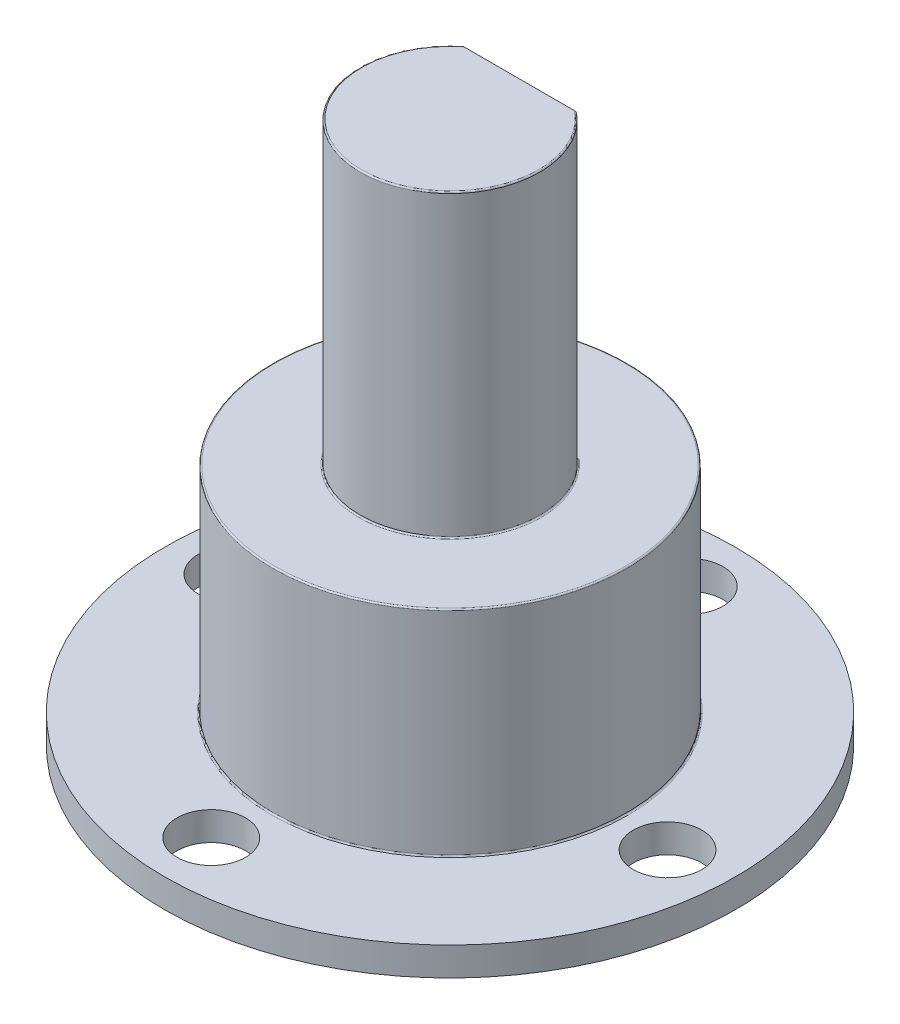
SolidWorks part; units mm, degrees
material "ABS"
ref_plane "Plan de face" through (0, 0, 0) normal (0, 0, 1) x (1, 0, 0)
ref_plane "Plan de dessus" through (0, 0, 0) normal (0, 1, 0) x (1, 0, 0)
ref_plane "Plan de droite" through (0, 0, 0) normal (1, 0, 0) x (0, 0, -1)
sketch "Esquisse2" plane through (0, 0, 0) normal (0, 0, 1) x (1, 0, 0)
  line L0 (0, 19) -> (3.15, 19)
  line L3 (6.2, 3) -> (6.2, 1)
  line L4 (6.2, 1) -> (10, 1)
  line L5 (10, 1) -> (10, 0)
  line L6 (10, 0) -> (4.5, 0)
  line L7 (4.5, 0) -> (4.5, 5)
  line L8 (4.5, 5) -> (0, 5)
  line L9 (0, 5) -> (0, 19)
  line L11 (3.15, 19) -> (3.15, 8.5)
  line L12 (3.15, 8.5) -> (6.2, 8.5)
  line L13 (6.2, 3) -> (6.2, 8.5)
  point P2 (1.575, 19)
  dimension "D1" = 10
  dimension "D2" = 19
  dimension "D3" = 0
  dimension "D4" = 1
  dimension "D5" = 4.5
  dimension "D6" = 2
  dimension "D7" = 8.5
  dimension "D8" = 5
  dimension "D9" = 3.15
  dimension "D10" = 0
  dimension "D12" = 1.7
revolve "Révolution2" add sketch "Esquisse2" angle 360 about L9
sketch "Esquisse3" plane through (0, 19, 0) normal (0, 1, 0) x (1, 0, 0)
  line L1 (-3.6413, 2.4219) -> (2.9365, 2.4219)
  line L2 (-3.6413, 2.4219) -> (-3.6413, 3.808)
  line L3 (-3.6413, 3.808) -> (2.9365, 3.808)
  line L4 (2.9365, 2.4219) -> (2.9365, 3.808)
  dimension "D1" = 6.5779
extrude "Enlèv. mat.-Extru.1" cut sketch "Esquisse3" against normal up to surface (10.5 mm away) contours L4 L3 L2 L1 up to face at (0, 8.5, -3.15)
hole_wizard "Dégagement M21" positions "Esquisse4" profile "Esquisse5" hole size "M2" standard "Ansi Metric" end condition up to next
sketch "Esquisse4" plane through (0, 1, 0) normal (0, 1, 0) x (1, 0, 0)
  circle A0 centre (0, 0) radius 8 construction
  point P0 (0.3713, 7.9914)
  dimension "D1" = 16
sketch "Esquisse5" plane through (0.3713, 1, -7.9914) normal (1, 0, 0) x (0, 0, 1)
  line L0 (0, 0) -> (0, 1.001)
  line L1 (0, 1.001) -> (1.2, 1.001)
  line L2 (1.2, 1.001) -> (1.2, 0)
  line L5 (1.2, 0) -> (0, 0)
  line L11 (0, -6.35) -> (0, 107.95) construction
  dimension "Diamètre du perçage jusqu'au prochain" = 2.4
  dimension "Profondeur du perçage jusqu'au prochain" = 1.001
pattern_circular "Répétition circulaire1" count 4 over 360 about axis through (0, 0, 0) along (0, 1, 0) of "Dégagement M21"
fillet "Congé1" radius 0.05 4 edges at (0, 8.5, 3.15) (0, 8.5, -6.2) (0, 1, -6.2) (0, 19, 3.15)
